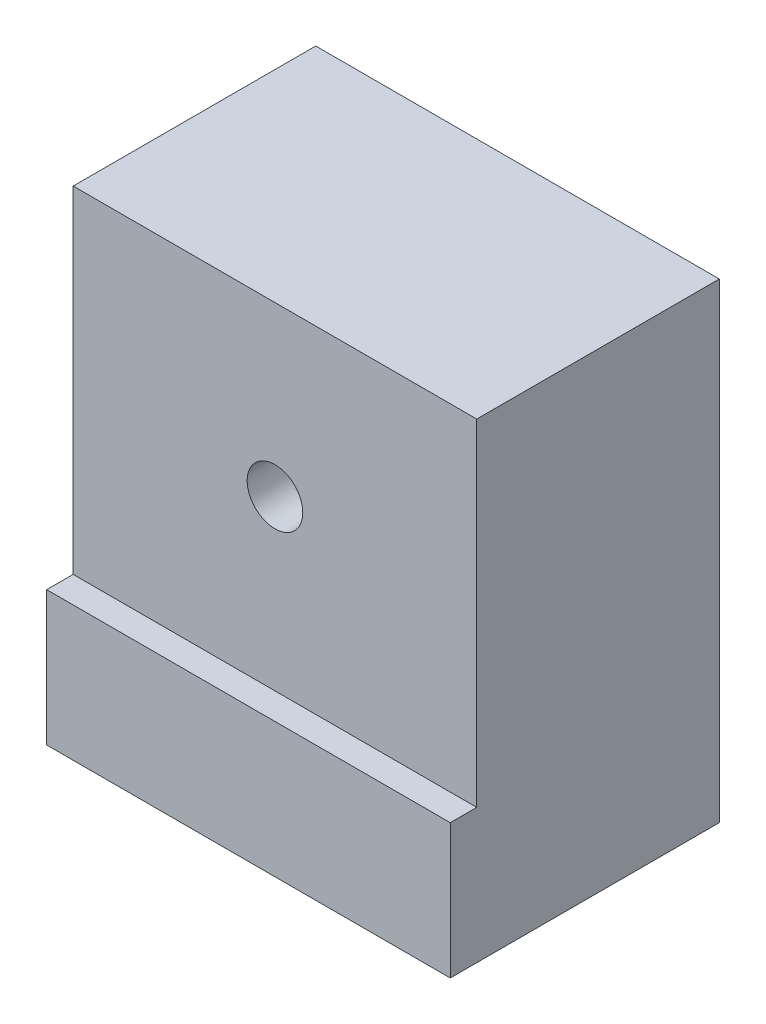
SolidWorks part; units mm, degrees
ref_plane "Front Plane" through (0, 0, 0) normal (0, 0, 1) x (1, 0, 0)
ref_plane "Top Plane" through (0, 0, 0) normal (0, 1, 0) x (1, 0, 0)
ref_plane "Right Plane" through (0, 0, 0) normal (1, 0, 0) x (0, 0, -1)
sketch "Sketch1" plane through (0, 0, 0) normal (0, 1, 0) x (1, 0, 0)
  line L1 (0, 0) -> (76.2, 0)
  line L2 (0, 0) -> (0, 50.8)
  line L3 (0, 50.8) -> (76.2, 50.8)
  line L4 (76.2, 0) -> (76.2, 50.8)
  dimension "D1" = 76.2
  dimension "D2" = 50.8
extrude "Boss-Extrude1" add sketch "Sketch1" along normal blind 88.9
sketch "Sketch2" plane through (0, 0, 0) normal (0, 0, 1) x (1, 0, 0)
  line L1 (0, 0) -> (38.1, 0)
  line L2 (0, 0) -> (0, 57.15)
  line L3 (0, 57.15) -> (38.1, 57.15)
  line L4 (38.1, 0) -> (38.1, 57.15)
  circle A0 centre (38.1, 57.15) radius 5.25
  dimension "D1" = 38.1
  dimension "D2" = 57.15
extrude "Cut-Extrude1" cut sketch "Sketch2" against normal blind 300 contours A0
sketch "Sketch3" plane through (0, 0, 0) normal (0, 0, 1) x (1, 0, 0)
  line L0 (76.2, 88.9) -> (76.2, 0) construction
  line L1 (0, 88.9) -> (76.2, 88.9)
  line L2 (0, 88.9) -> (0, 25.4)
  line L3 (0, 25.4) -> (76.2, 25.4)
  line L4 (76.2, 88.9) -> (76.2, 25.4)
  dimension "D1" = 63.5
extrude "Cut-Extrude2" cut sketch "Sketch3" against normal blind 5
sketch "Sketch5" plane through (0, 88.9, 0) normal (0, 1, 0) x (1, 0, 0)
  line L0 (0, 5) -> (0, 30.4)
  line L1 (0, 50.8) -> (0, 5) construction
  line L2 (0, 30.4) -> (45.8, 50.8)
  line L3 (76.2, 50.8) -> (0, 50.8) construction
  line L4 (45.8, 50.8) -> (76.2, 50.8)
  line L5 (45.8, 50.8) -> (0, 50.8)
  line L6 (0, 50.8) -> (0, 30.4)
  dimension "D1" = 30.4
  dimension "D2" = 25.4
